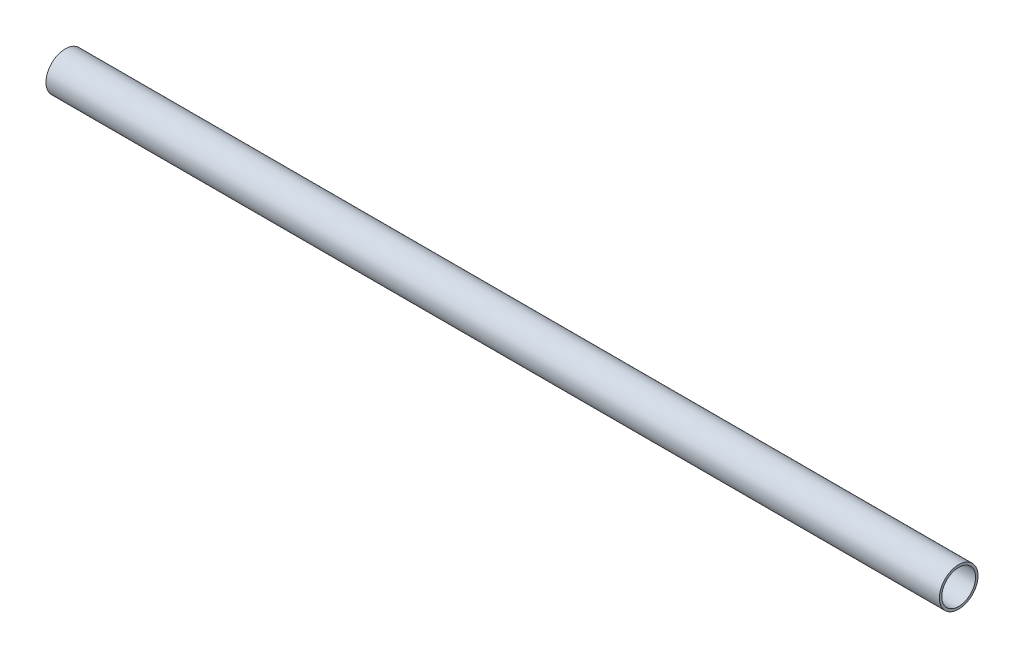
SolidWorks part; units mm, degrees
material "Thornel Mat VMA"
ref_plane "前视基准面" through (0, 0, 0) normal (0, 0, 1) x (1, 0, 0)
ref_plane "上视基准面" through (0, 0, 0) normal (0, 1, 0) x (1, 0, 0)
ref_plane "右视基准面" through (0, 0, 0) normal (1, 0, 0) x (0, 0, -1)
sketch "草图1" plane through (0, 0, 0) normal (1, 0, 0) x (0, 0, -1)
  circle A0 centre (0, 0) radius 8
  circle A1 centre (0, 0) radius 7
  dimension "D1" = 16
  dimension "D2" = 1
extrude "凸台-拉伸1" add sketch "草图1" along normal mid plane 370
